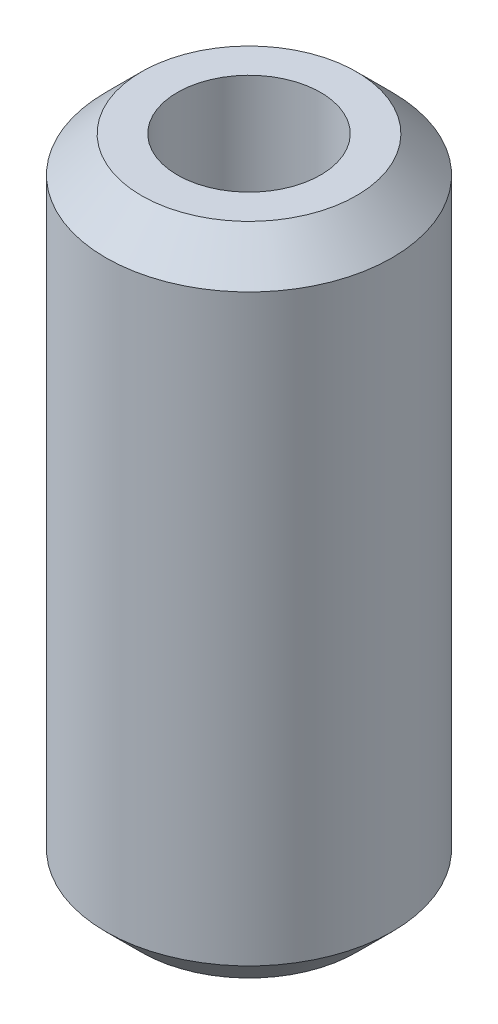
SolidWorks part; units mm, degrees
ref_plane "Спереди" through (0, 0, 0) normal (0, 0, 1) x (1, 0, 0)
ref_plane "Сверху" through (0, 0, 0) normal (0, 1, 0) x (1, 0, 0)
ref_plane "Справа" through (0, 0, 0) normal (1, 0, 0) x (0, 0, -1)
sketch "Эскиз1" plane through (0, 0, 0) normal (0, 1, 0) x (1, 0, 0)
  circle A0 centre (0, 0) radius 2
  circle A1 centre (0, 0) radius 4
  dimension "D1" = 4
  dimension "D2" = 8
extrude "Бобышка-Вытянуть1" add sketch "Эскиз1" along normal blind 18.3
chamfer "Фаска1" distance 1 angle 45 2 edges at (0, 0, 4) (0, 18.3, 4)
